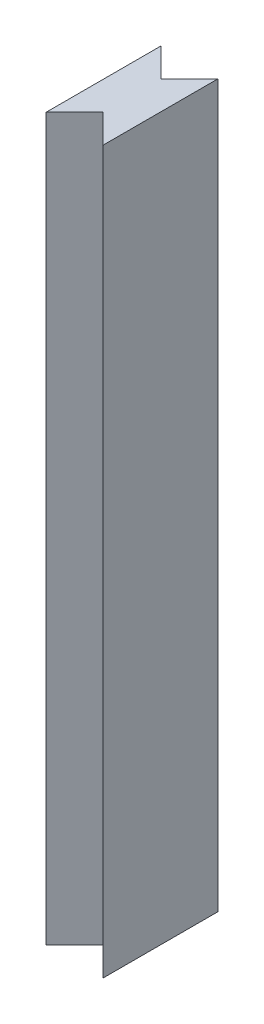
SolidWorks part; units mm, degrees
ref_plane "Alzado" through (0, 0, 0) normal (0, 0, 1) x (1, 0, 0)
ref_plane "Planta" through (0, 0, 0) normal (0, 1, 0) x (1, 0, 0)
ref_plane "Vista lateral" through (0, 0, 0) normal (1, 0, 0) x (0, 0, -1)
sketch "Croquis1" plane through (0, 0, 0) normal (0, 1, 0) x (1, 0, 0)
  line L0 (13.2185, 0) -> (-13.2185, 0) construction
  line L1 (1.975, 3.975) -> (0, 2)
  line L5 (-1.975, -3.975) -> (-1.975, 3.975)
  line L7 (0, -13.2185) -> (0, 13.2185) construction
  line L10 (1.975, 3.975) -> (1.975, -3.975)
  line L14 (-1.975, 3.975) -> (0, 2)
  line L17 (0, -2) -> (-1.975, -3.975)
  line L19 (1.975, -3.975) -> (0, -2)
  point P0 (0, 0)
  point P1 (0, 0)
  point P2 (0, 0)
  point P11 (0, 0)
  point P16 (-1.975, 3.975)
  point P20 (1.975, 3.975)
  point P29 (-1.975, -3.975)
  point P30 (1.975, -3.975)
  point P31 (0, -2)
  dimension "D2" = 2
  dimension "D3" = 7.95
  dimension "D4" = 1.975
  dimension "D5" = 1.4142
  dimension "D6" = 1.4142
  dimension "D8" = 1.4142
  dimension "D9" = 1.975
  dimension "D10" = 1.975
  dimension "D11" = 1.975
extrude "Saliente-Extruir1" add sketch "Croquis1" along normal blind 50
